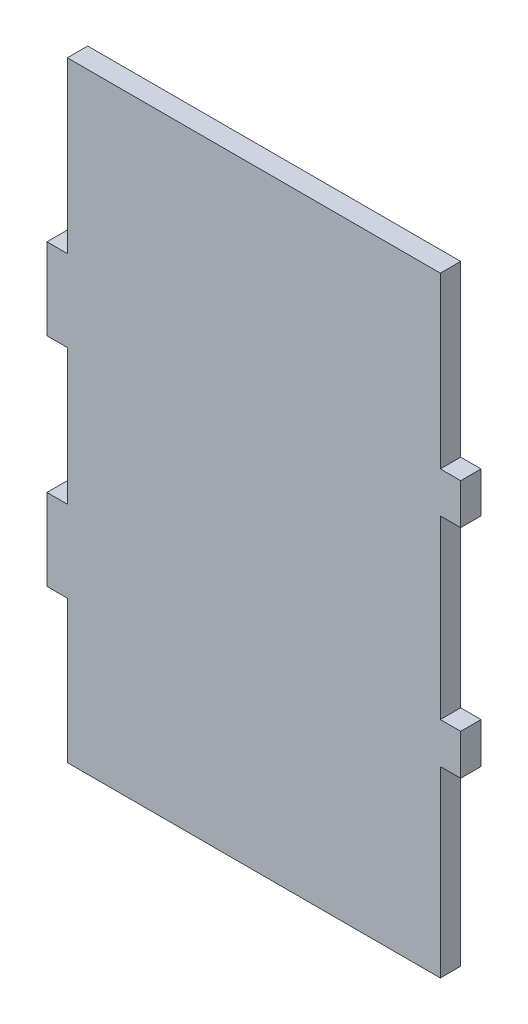
SolidWorks part; units mm, degrees
ref_plane "Přední rovina" through (0, 0, 0) normal (0, 0, 1) x (1, 0, 0)
ref_plane "Horní rovina" through (0, 0, 0) normal (0, 1, 0) x (1, 0, 0)
ref_plane "Pravá rovina" through (0, 0, 0) normal (1, 0, 0) x (0, 0, -1)
sketch "Skica1" plane through (0, 0, 0) normal (0, 0, 1) x (1, 0, 0)
  line L0 (0, 0) -> (55, 0)
  line L1 (0, 0) -> (0, -25)
  line L2 (55, 0) -> (55, -25)
  line L3 (0, -90) -> (55, -90)
  line L5 (0, -25) -> (-3, -25)
  line L6 (0, -37) -> (-3, -37)
  line L7 (-3, -25) -> (-3, -37)
  line L8 (0, -57) -> (-3, -57)
  line L9 (0, -69) -> (-3, -69)
  line L10 (-3, -57) -> (-3, -69)
  line L11 (55, -63) -> (58, -63)
  line L12 (58, -57) -> (58, -63)
  line L13 (55, -57) -> (58, -57)
  line L14 (55, -25) -> (58, -25)
  line L15 (55, -31) -> (58, -31)
  line L16 (58, -25) -> (58, -31)
  line L17 (55, -63) -> (55, -90)
  line L18 (55, -31) -> (55, -57)
  line L19 (0, -37) -> (0, -57)
  line L20 (0, -69) -> (0, -90)
  dimension "D1" = 55
  dimension "D2" = 90
  dimension "D3" = 3
  dimension "D4" = 3
  dimension "D5" = 12
  dimension "D6" = 12
  dimension "D7" = 25
  dimension "D8" = 20
  dimension "D9" = 6
  dimension "D10" = 6
  dimension "D11" = 25
  dimension "D12" = 26
  dimension "D13" = 3
  dimension "D14" = 3
extrude "Přidat vysunutím1" add sketch "Skica1" along normal blind 3
